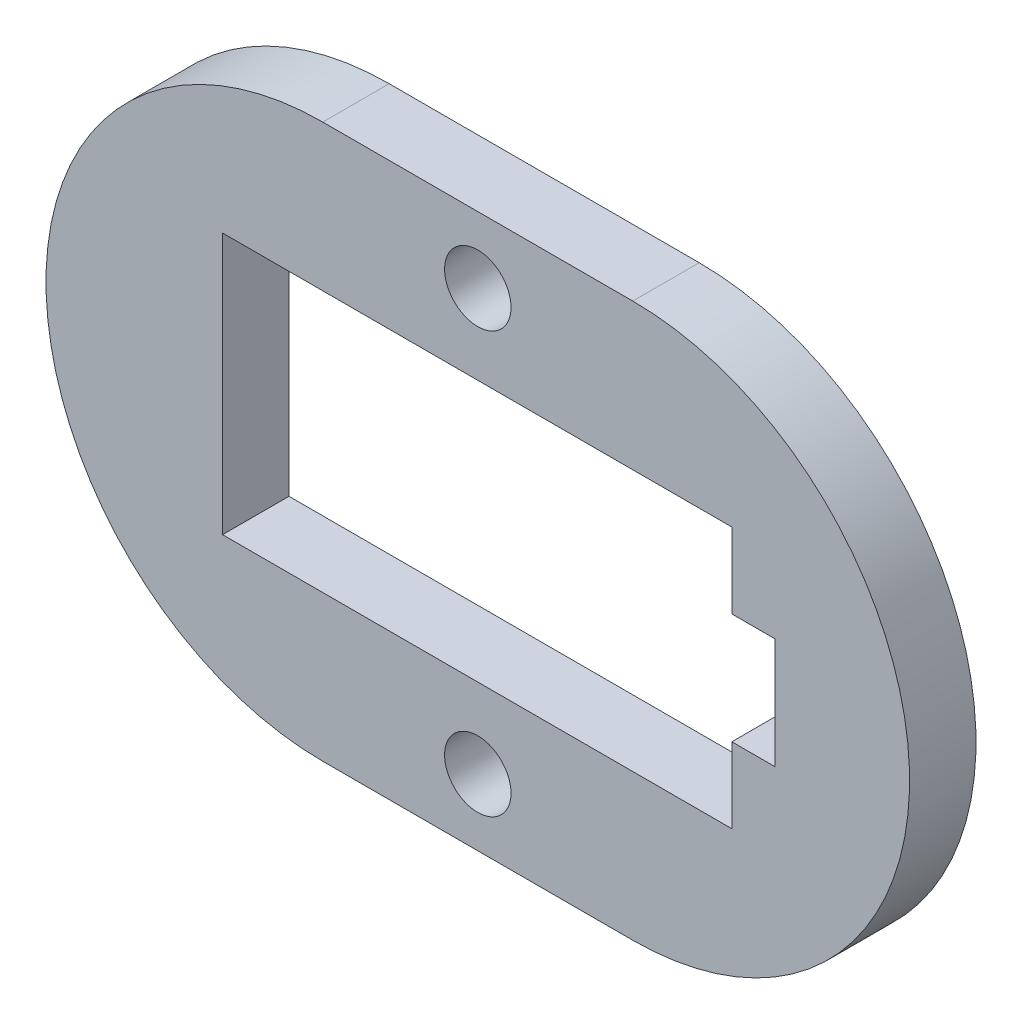
SolidWorks part; units mm, degrees
ref_plane "Plan de face" through (0, 0, 0) normal (0, 0, 1) x (1, 0, 0)
ref_plane "Plan de dessus" through (0, 0, 0) normal (0, 1, 0) x (1, 0, 0)
ref_plane "Plan de droite" through (0, 0, 0) normal (1, 0, 0) x (0, 0, -1)
sketch "Esquisse2" plane through (0, 0, 0) normal (0, 0, 1) x (1, 0, 0)
  line L1 (0, 0) -> (0, 11.8)
  line L10 (4.5267, 18.4) -> (18.5267, 18.4)
  line L11 (0, 11.8) -> (23, 11.8)
  line L12 (23, 8.4) -> (23, 11.8)
  line L13 (24.9403, 8.4) -> (23, 8.4)
  line L14 (24.9403, 8.4) -> (24.9403, 3.4)
  line L15 (24.9403, 3.4) -> (23, 3.4)
  line L16 (23, 0) -> (23, 3.4)
  line L17 (0, 0) -> (23, 0)
  line L19 (4.5267, -6.6) -> (18.5267, -6.6)
  arc A1 (4.5267, 18.4) -> (4.5267, -6.6) centre (4.5267, 5.9) ccw
  circle A4 centre (11.5267, 15.4) radius 1.5
  circle A5 centre (11.5267, -3.6) radius 1.5
  arc A7 (18.5267, -6.6) -> (18.5267, 18.4) centre (18.5267, 5.9) ccw
  dimension "D1" = 23
  dimension "D2" = 12.5
  dimension "D4" = 3
  dimension "D5" = 3
  dimension "D6" = 19
  dimension "D7" = 9.5
  dimension "D3" = 14
  dimension "D8" = 5
  dimension "D9" = 3.4
  dimension "D10" = 14
  dimension "D11" = 5.9
  dimension "D12" = 11.8
  dimension "D13" = 23
extrude "Boss.-Extru.2" add sketch "Esquisse2" along normal blind 3
